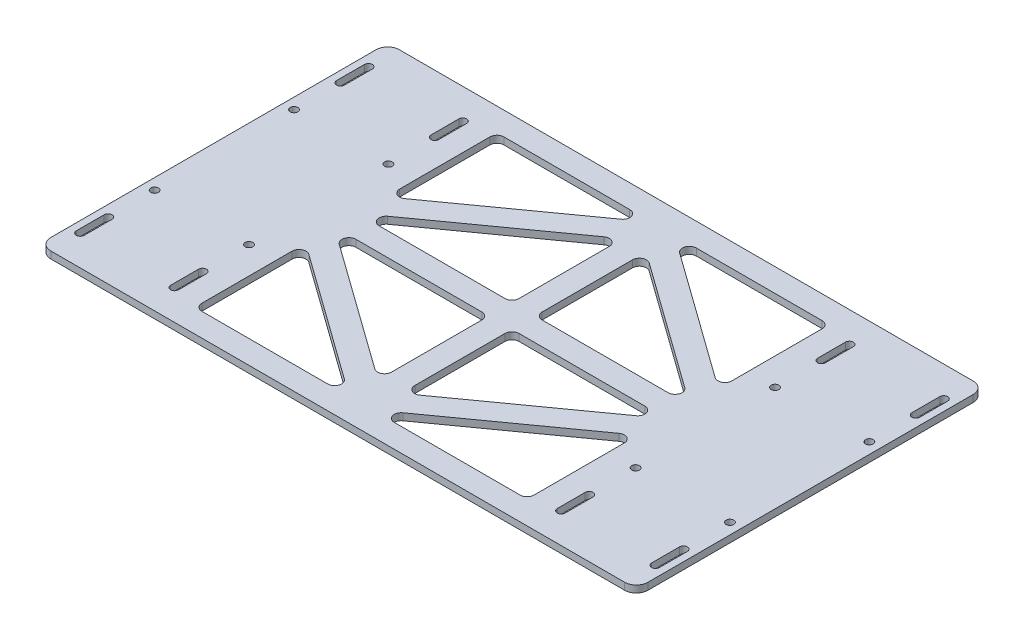
SolidWorks part; units mm, degrees
material "Thornel Mat VMA"
ref_plane "前视基准面" through (0, 0, 0) normal (0, 0, 1) x (1, 0, 0)
ref_plane "上视基准面" through (0, 0, 0) normal (0, 1, 0) x (1, 0, 0)
ref_plane "右视基准面" through (0, 0, 0) normal (1, 0, 0) x (0, 0, -1)
sketch "草图1" plane through (0, 0, 0) normal (0, 1, 0) x (1, 0, 0)
  line L0 (0, 75) -> (257, 75) construction
  line L1 (0, 0) -> (257, 0)
  line L2 (0, 0) -> (0, 150)
  line L3 (0, 150) -> (257, 150)
  line L4 (257, 0) -> (257, 150)
  line L5 (128.5, 150) -> (128.5, 0) construction
  line L6 (25, 150) -> (25, 0) construction
  line L7 (4.7, 137) -> (4.7, 125) construction
  line L8 (6.4, 137) -> (6.4, 125)
  line L9 (3, 137) -> (3, 125)
  line L10 (45.3, 137) -> (45.3, 125) construction
  line L11 (43.6, 137) -> (43.6, 125)
  line L12 (47, 137) -> (47, 125)
  line L13 (45.3, 13) -> (45.3, 25) construction
  line L14 (43.6, 13) -> (43.6, 25)
  line L15 (47, 13) -> (47, 25)
  line L16 (4.7, 13) -> (4.7, 25) construction
  line L17 (6.4, 13) -> (6.4, 25)
  line L18 (3, 13) -> (3, 25)
  line L19 (211.7, 13) -> (211.7, 25) construction
  line L20 (213.4, 13) -> (213.4, 25)
  line L21 (210, 13) -> (210, 25)
  line L22 (252.3, 13) -> (252.3, 25) construction
  line L23 (250.6, 13) -> (250.6, 25)
  line L24 (254, 13) -> (254, 25)
  line L25 (252.3, 137) -> (252.3, 125) construction
  line L26 (250.6, 137) -> (250.6, 125)
  line L27 (254, 137) -> (254, 125)
  line L28 (211.7, 137) -> (211.7, 125) construction
  line L29 (213.4, 137) -> (213.4, 125)
  line L30 (210, 137) -> (210, 125)
  arc A0 (6.4, 137) -> (3, 137) centre (4.7, 137) ccw
  arc A1 (3, 125) -> (6.4, 125) centre (4.7, 125) ccw
  arc A2 (43.6, 137) -> (47, 137) centre (45.3, 137) cw
  arc A3 (47, 125) -> (43.6, 125) centre (45.3, 125) cw
  arc A4 (43.6, 13) -> (47, 13) centre (45.3, 13) ccw
  arc A5 (47, 25) -> (43.6, 25) centre (45.3, 25) ccw
  arc A6 (6.4, 13) -> (3, 13) centre (4.7, 13) cw
  arc A7 (3, 25) -> (6.4, 25) centre (4.7, 25) cw
  arc A8 (213.4, 13) -> (210, 13) centre (211.7, 13) cw
  arc A9 (210, 25) -> (213.4, 25) centre (211.7, 25) cw
  arc A10 (250.6, 13) -> (254, 13) centre (252.3, 13) ccw
  arc A11 (254, 25) -> (250.6, 25) centre (252.3, 25) ccw
  arc A12 (250.6, 137) -> (254, 137) centre (252.3, 137) cw
  arc A13 (254, 125) -> (250.6, 125) centre (252.3, 125) cw
  arc A14 (213.4, 137) -> (210, 137) centre (211.7, 137) ccw
  arc A15 (210, 125) -> (213.4, 125) centre (211.7, 125) ccw
  circle A16 centre (4.7, 45) radius 1.65
  circle A17 centre (4.7, 105) radius 1.65
  circle A18 centre (45.3, 45) radius 1.65
  circle A19 centre (45.3, 105) radius 1.65
  circle A20 centre (252.3, 105) radius 1.65
  circle A21 centre (211.7, 105) radius 1.65
  circle A22 centre (252.3, 45) radius 1.65
  circle A23 centre (211.7, 45) radius 1.65
  point P13 (4.7, 131)
  point P20 (45.3, 131)
  point P27 (45.3, 19)
  point P34 (4.7, 19)
  point P41 (211.7, 19)
  point P48 (252.3, 19)
  point P55 (252.3, 131)
  point P62 (211.7, 131)
  dimension "D8" = 60
  dimension "D9" = 3.3
  dimension "D1" = 257
  dimension "D2" = 150
  dimension "D3" = 25
  dimension "D4" = 44
  dimension "D5" = 3.4
  dimension "D6" = 12
  dimension "D7" = 100
extrude "凸台-拉伸1" add sketch "草图1" along normal blind 3
sketch "草图2" plane through (0, 3, 0) normal (0, 1, 0) x (1, 0, 0)
  line L0 (128.5, 150) -> (128.5, 0) construction
  line L1 (257, 150) -> (0, 150) construction
  line L2 (0, 0) -> (257, 0) construction
  line L3 (57, 140) -> (123.5, 140)
  line L4 (123.5, 140) -> (57, 92.306)
  line L5 (57, 92.306) -> (57, 140)
  line L6 (57, 80) -> (123.5, 127.694)
  line L7 (123.5, 127.694) -> (123.5, 80)
  line L8 (123.5, 80) -> (57, 80)
  line L9 (0, 75) -> (257, 75) construction
  line L10 (0, 150) -> (0, 0) construction
  line L11 (257, 0) -> (257, 150) construction
  line L12 (47, 125) -> (47, 137) construction
  line L13 (133.5, 80) -> (200, 80)
  line L14 (133.5, 127.694) -> (133.5, 80)
  line L15 (200, 80) -> (133.5, 127.694)
  line L16 (200, 92.306) -> (200, 140)
  line L17 (133.5, 140) -> (200, 92.306)
  line L18 (200, 140) -> (133.5, 140)
  line L19 (200, 10) -> (133.5, 10)
  line L20 (133.5, 10) -> (200, 57.694)
  line L21 (200, 57.694) -> (200, 10)
  line L22 (200, 70) -> (133.5, 22.306)
  line L23 (133.5, 22.306) -> (133.5, 70)
  line L24 (133.5, 70) -> (200, 70)
  line L25 (123.5, 70) -> (57, 70)
  line L26 (123.5, 22.306) -> (123.5, 70)
  line L27 (57, 70) -> (123.5, 22.306)
  line L28 (57, 57.694) -> (57, 10)
  line L29 (123.5, 10) -> (57, 57.694)
  line L30 (57, 10) -> (123.5, 10)
  dimension "D1" = 5
  dimension "D2" = 5
  dimension "D3" = 10
  dimension "D4" = 10
  dimension "D5" = 10
extrude "切除-拉伸1" cut sketch "草图2" against normal through all
fillet "圆角1" radius 3 24 edges at (123.5, 1.5, -22.306) (57, 1.5, -10) (123.5, 1.5, -10) (57, 1.5, -70) (57, 1.5, -57.694) (123.5, 1.5, -70) (200, 1.5, -70) (133.5, 1.5, -70) (133.5, 1.5, -22.306) (133.5, 1.5, -10) (200, 1.5, -57.694) (200, 1.5, -10) (200, 1.5, -92.306) (200, 1.5, -140) (133.5, 1.5, -140) (133.5, 1.5, -127.694) (200, 1.5, -80) (133.5, 1.5, -80) (123.5, 1.5, -80) (123.5, 1.5, -140) (123.5, 1.5, -127.694) (57, 1.5, -140) (57, 1.5, -92.306) (57, 1.5, -80)
fillet "圆角2" radius 5 4 edges at (0, 1.5, -150) (257, 1.5, -150) (257, 1.5, 0) (0, 1.5, 0)
